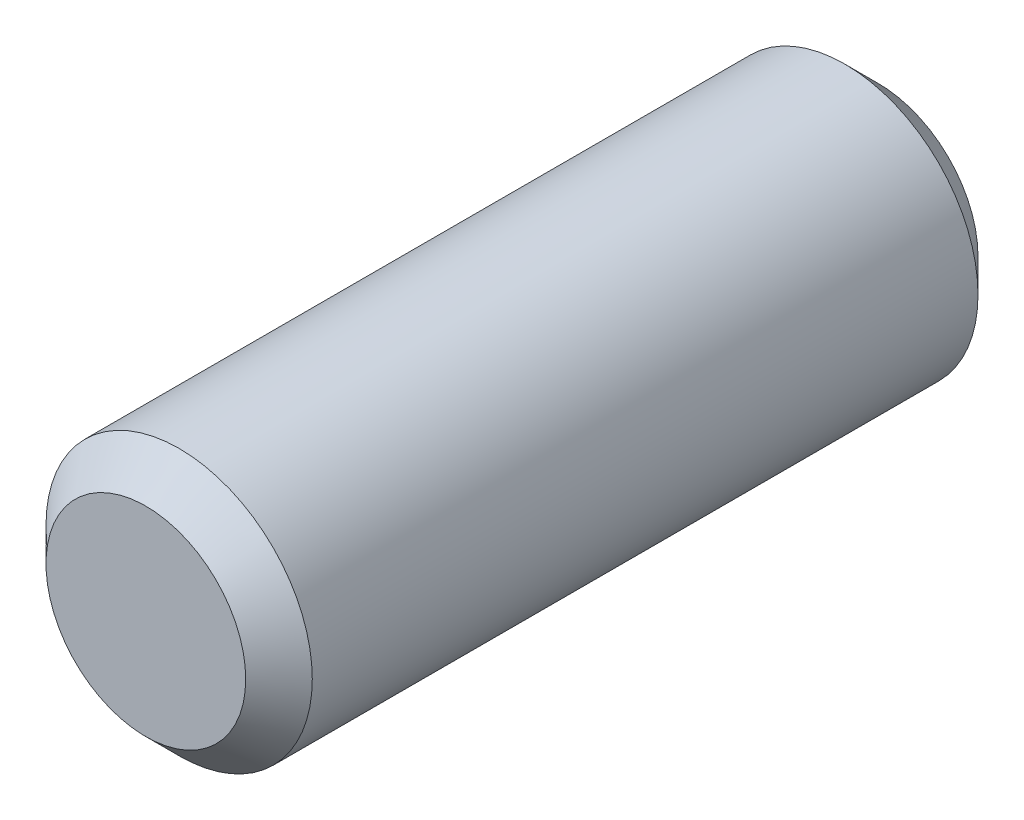
SolidWorks part; units mm, degrees
ref_plane "Plan de face" through (0, 0, 0) normal (0, 0, 1) x (1, 0, 0)
ref_plane "Plan de dessus" through (0, 0, 0) normal (0, 1, 0) x (1, 0, 0)
ref_plane "Plan de droite" through (0, 0, 0) normal (1, 0, 0) x (0, 0, -1)
sketch "Esquisse1" plane through (0, 0, 0) normal (0, 0, 1) x (1, 0, 0)
  circle A0 centre (0, 0) radius 2
  dimension "D1" = 4
extrude "Boss.-Extru.1" add sketch "Esquisse1" along normal mid plane 11
chamfer "Chanfrein1" distance 0.5 angle 45 2 edges at (2, 0, -5.5) (2, 0, 5.5)
